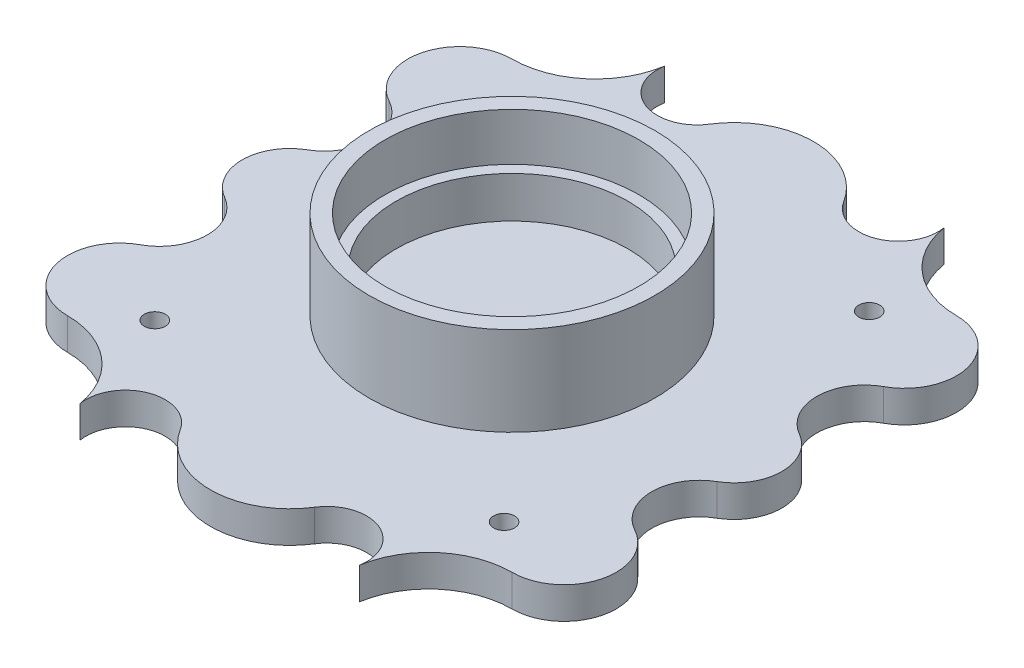
SolidWorks part; units mm, degrees
ref_plane "Alzado" through (0, 0, 0) normal (0, 0, 1) x (1, 0, 0)
ref_plane "Planta" through (0, 0, 0) normal (0, 1, 0) x (1, 0, 0)
ref_plane "Vista lateral" through (0, 0, 0) normal (1, 0, 0) x (0, 0, -1)
sketch "Croquis1" plane through (0, 0, 0) normal (0, 1, 0) x (1, 0, 0)
  line L0 (0, 138.5041) -> (0, -177.2184) construction
  line L2 (-70, -70) -> (-70, 70)
  line L4 (70, -70) -> (70, 70)
  line L5 (-70, -70) -> (70, 70) construction
  line L6 (-70, 70) -> (70, -70) construction
  line L7 (-103.4324, 0) -> (144.2109, 0) construction
  arc A1 (-21.1476, -83.3333) -> (21.1476, -83.3333) centre (0, -70) ccw
  arc A5 (-21.1476, -83.3333) -> (-44.0559, -92.0276) centre (-31.7214, -90) ccw
  arc A6 (-44.0559, -92.0276) -> (-70, -70) centre (-70, -96.2923) ccw
  arc A7 (21.1476, -83.3333) -> (44.0559, -92.0276) centre (31.7214, -90) cw
  arc A8 (44.0559, -92.0276) -> (70, -70) centre (70, -96.2923) cw
  arc A9 (44.0559, 92.0276) -> (70, 70) centre (70, 96.2923) ccw
  arc A10 (21.1476, 83.3333) -> (44.0559, 92.0276) centre (31.7214, 90) ccw
  arc A11 (-21.1476, 83.3333) -> (21.1476, 83.3333) centre (0, 70) cw
  arc A12 (-21.1476, 83.3333) -> (-44.0559, 92.0276) centre (-31.7214, 90) cw
  arc A13 (-44.0559, 92.0276) -> (-70, 70) centre (-70, 96.2923) cw
  point P0 (0, 0)
  point P14 (-25, -70)
  point P16 (-70, -70)
  dimension "D4" = 50
  dimension "D6" = 25
  dimension "D1" = 140
  dimension "D2" = 140
extrude "Saliente-Extruir1" add sketch "Croquis1" along normal blind 10
sketch "Croquis2" plane through (0, 10, 0) normal (0, 1, 0) x (1, 0, 0)
  line L0 (70, -70) -> (70, 70) construction
  line L1 (70, 70) -> (70, -70)
  line L2 (0, 152.4123) -> (0, -148.5895) construction
  line L3 (-96.3545, 0) -> (168.0513, 0) construction
  line L4 (-70, 70) -> (-70, -70)
  arc A0 (77.5, -12.9904) -> (77.5, 12.9904) centre (70, 0) ccw
  arc A1 (77.838, 39.1605) -> (77.5, 12.9904) centre (85, 25.9808) ccw
  arc A2 (77.838, 39.1605) -> (70, 70) centre (70, 53.5842) ccw
  arc A3 (77.838, -39.1605) -> (77.5, -12.9904) centre (85, -25.9808) cw
  arc A4 (77.838, -39.1605) -> (70, -70) centre (70, -53.5842) cw
  arc A5 (-77.838, -39.1605) -> (-70, -70) centre (-70, -53.5842) ccw
  arc A6 (-77.838, -39.1605) -> (-77.5, -12.9904) centre (-85, -25.9808) ccw
  arc A7 (-77.5, -12.9904) -> (-77.5, 12.9904) centre (-70, 0) cw
  arc A8 (-77.838, 39.1605) -> (-77.5, 12.9904) centre (-85, 25.9808) cw
  arc A9 (-77.838, 39.1605) -> (-70, 70) centre (-70, 53.5842) cw
  line M11 (-70, 70) -> (-70, -70)
  line M17 (70, -70) -> (70, 70)
  dimension "D1" = 30
  dimension "D2" = 30
extrude "Saliente-Extruir2" add sketch "Croquis2" against normal blind 10 contours A9 A8 M11 | A1 A2 L1 | L1 A3 A0 A1 | L4 A8 A7 A6 | A6 A5 L4 | A4 A3 M17
sketch "Croquis3" plane through (0, 10, 0) normal (0, 1, 0) x (1, 0, 0)
  circle A0 centre (0, 0) radius 40
  circle A1 centre (0, 0) radius 36.5
  dimension "D1" = 80
  dimension "D2" = 73
extrude "Saliente-Extruir3" add sketch "Croquis3" along normal blind 13
sketch "Croquis4" plane through (0, 10, 0) normal (0, 1, 0) x (1, 0, 0)
  circle A0 centre (0, 0) radius 45
  circle A1 centre (0, 0) radius 40
  circle A2 centre (0, 0) radius 40 construction
  dimension "D1" = 90
extrude "Saliente-Extruir4" add sketch "Croquis4" along normal blind 28
hole_wizard "Refrentado para tornillo con cabeza hueca hexagonal de M61" positions "Croquis3D1" profile "Croquis5" counterbore size "M6" standard "DIN"
sketch3d "Croquis3D1"
  line L1 (-55, 0, -57.5) -> (-55, 0, 57.5) construction
  line L2 (-55, 0, -57.5) -> (55, 0, -57.5) construction
  line L3 (55, 0, -57.5) -> (55, 0, 57.5) construction
  line L4 (-55, 0, 57.5) -> (55, 0, 57.5) construction
  line L5 (-55, 0, -57.5) -> (55, 0, 57.5) construction
  line L6 (55, 0, -57.5) -> (-55, 0, 57.5) construction
  point P0 (-55, 0, 57.5)
  point P2 (55, 0, 57.5)
  point P4 (55, 0, -57.5)
  point P6 (-55, 0, -57.5)
  point P9 (0, 0, 0)
  point P116 (0, 0, 0)
  point P117 (0, 0, 0)
  point P118 (0, 0, 0)
  dimension "D1" = 115
  dimension "D2" = 110
sketch "Croquis5" plane through (-55, 0, 57.5) normal (1, 0, 0) x (0, 0, -1)
  line L0 (0, 0) -> (0, 10)
  line L1 (0, 10) -> (3.3, 10)
  line L3 (3.3, 10) -> (3.3, 4.6)
  line L4 (3.3, 4.6) -> (5.5, 4.6)
  line L5 (5.5, 4.6) -> (5.5, 0)
  line L7 (5.5, 0) -> (0, 0)
  line L11 (0, -6.35) -> (0, 107.95) construction
  dimension "Diámetro de taladro hasta el siguiente" = 6.6
  dimension "Profundidad de taladro hasta el siguiente" = 10
  dimension "Diámetro de refrentado" = 11
  dimension "Profundidad de refrentado" = 4.6
